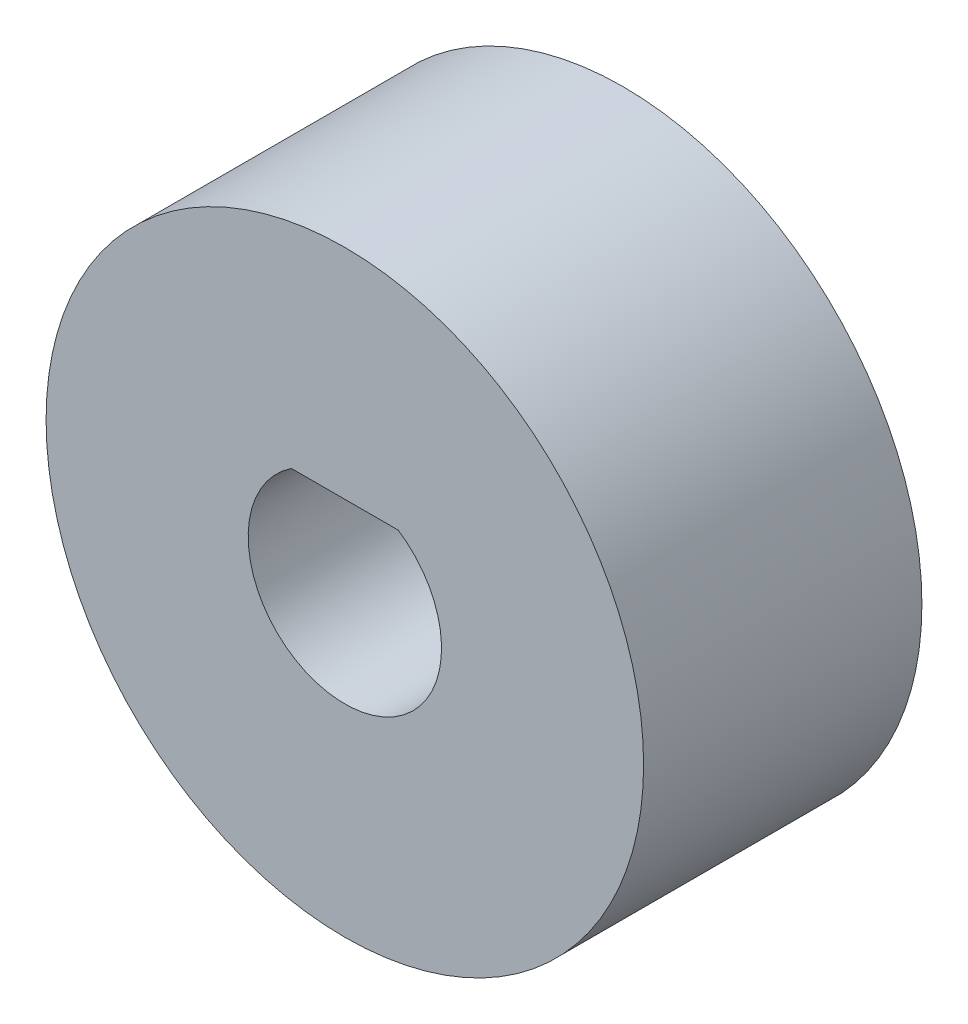
SolidWorks part; units mm, degrees
ref_plane "Front Plane" through (0, 0, 0) normal (0, 0, 1) x (1, 0, 0)
ref_plane "Top Plane" through (0, 0, 0) normal (0, 1, 0) x (1, 0, 0)
ref_plane "Right Plane" through (0, 0, 0) normal (1, 0, 0) x (0, 0, -1)
sketch "Sketch1" plane through (0, 0, 0) normal (0, 0, 1) x (1, 0, 0)
  line L1 (1.6583, 2.5) -> (-1.6583, 2.5)
  circle A0 centre (0, 0) radius 9.271
  arc A1 (-1.6583, 2.5) -> (1.6583, 2.5) centre (0, 0) ccw
  dimension "D1" = 18.542
  dimension "D2" = 6
extrude "Boss-Extrude1" add sketch "Sketch1" along normal blind 8.636
